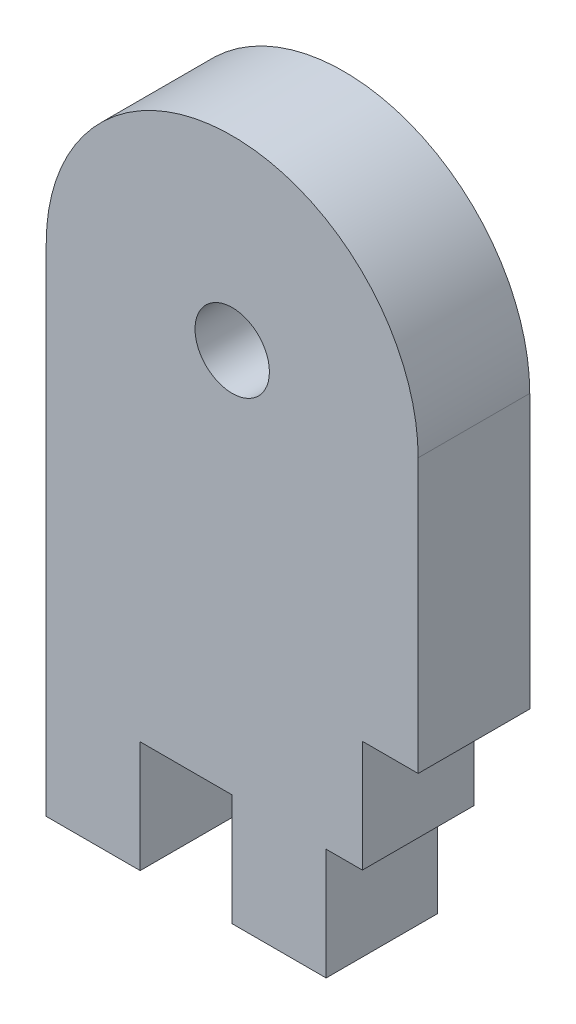
SolidWorks part; units mm, degrees
ref_plane "Plan de face" through (0, 0, 0) normal (0, 0, 1) x (1, 0, 0)
ref_plane "Plan de dessus" through (0, 0, 0) normal (0, 1, 0) x (1, 0, 0)
ref_plane "Plan de droite" through (0, 0, 0) normal (1, 0, 0) x (0, 0, -1)
sketch "Esquisse1" plane through (0, 0, 0) normal (0, 0, 1) x (1, 0, 0)
  line L0 (0, 0) -> (0, 26.7)
  line L2 (20, 26.7) -> (20, 12)
  line L3 (20, 12) -> (17, 12)
  line L4 (17, 12) -> (17, 6)
  line L5 (17, 6) -> (15.05, 6)
  line L6 (15.05, 6) -> (15.05, 0)
  line L7 (15.05, 0) -> (10, 0)
  line L8 (10, 0) -> (10, 6)
  line L9 (10, 6) -> (5.05, 6)
  line L10 (5.05, 6) -> (5.05, 0)
  line L11 (5.05, 0) -> (0, 0)
  line L12 (2.525, 0) -> (2.525, 6) construction
  circle A0 centre (10, 26.7) radius 2
  arc A1 (20, 26.7) -> (0, 26.7) centre (10, 26.7) ccw
  dimension "D8" = 4
  dimension "D1" = 5.05
  dimension "D2" = 4.95
  dimension "D3" = 4.95
  dimension "D4" = 6
  dimension "D5" = 6
  dimension "D6" = 7.475
  dimension "D7" = 3
  dimension "D9" = 20.7
extrude "Boss.-Extru.1" add sketch "Esquisse1" along normal blind 6
